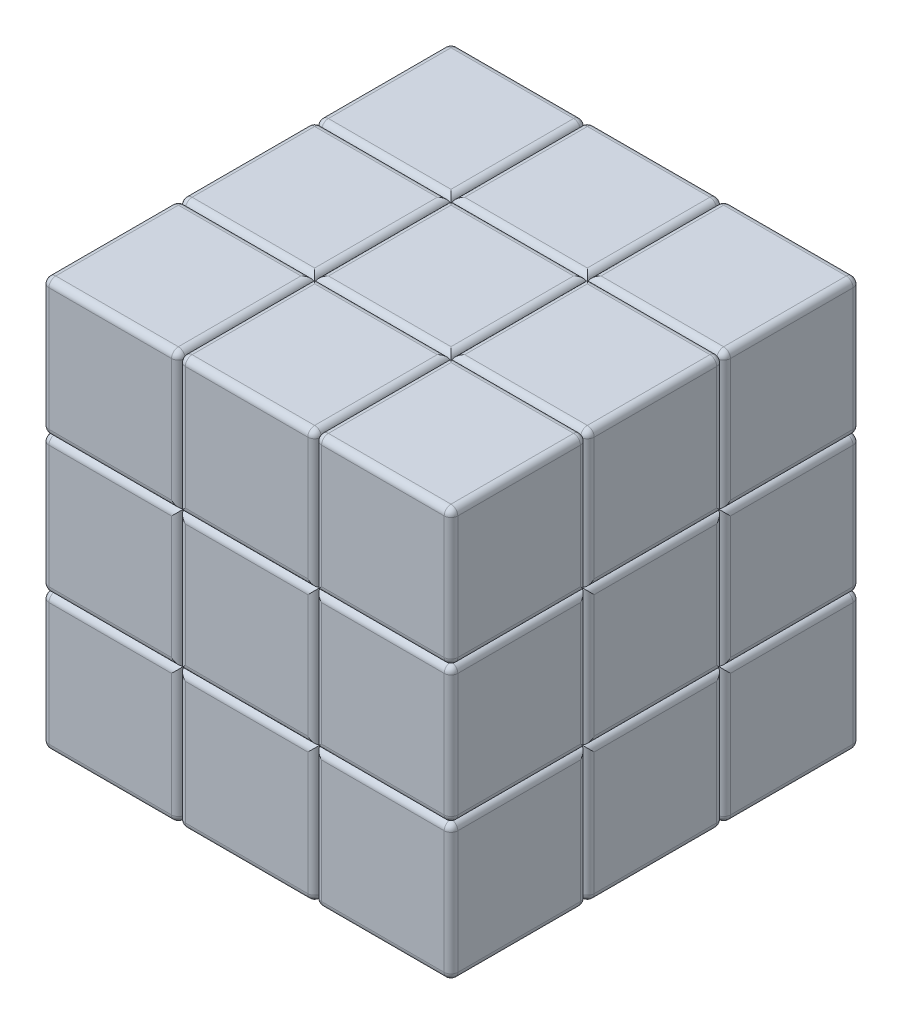
SolidWorks part; units mm, degrees
material "PA Type 6"
ref_plane "Front Plane" through (0, 0, 0) normal (0, 0, 1) x (1, 0, 0)
ref_plane "Top Plane" through (0, 0, 0) normal (0, 1, 0) x (1, 0, 0)
ref_plane "Right Plane" through (0, 0, 0) normal (1, 0, 0) x (0, 0, -1)
sketch "Sketch1" plane through (0, 0, 0) normal (0, 0, 1) x (1, 0, 0)
  line L1 (-41.2998, 31.3933) -> (18.7002, 31.3933)
  line L2 (-41.2998, 31.3933) -> (-41.2998, -28.6067)
  line L3 (-41.2998, -28.6067) -> (18.7002, -28.6067)
  line L4 (18.7002, 31.3933) -> (18.7002, -28.6067)
  dimension "D1" = 60
  dimension "D2" = 60
extrude "Boss-Extrude1" add sketch "Sketch1" along normal blind 60
sketch "Sketch2" plane through (0, 0, 60) normal (0, 0, 1) x (1, 0, 0)
  line L0 (-1.2898, -8.5967) -> (18.7002, -8.5967)
  line L3 (-21.2898, 11.3833) -> (-1.3098, 11.3833)
  line L4 (-21.2898, 11.3833) -> (-21.2898, -8.5967)
  line L7 (-1.2898, -8.6167) -> (18.7002, -8.6167)
  line L8 (-21.3098, 31.3933) -> (-21.3098, 11.4033)
  line L9 (-21.2898, 31.3933) -> (-21.2898, 11.4033)
  line L10 (-21.3098, 31.3933) -> (-21.2898, 31.3933)
  line L11 (-21.3098, -28.6067) -> (-21.2898, -28.6067)
  line L12 (-1.2898, -8.6167) -> (-1.2898, -28.6067)
  line L13 (-41.2998, 11.3833) -> (-21.3098, 11.3833)
  line L14 (-41.2998, -8.6167) -> (-21.3098, -8.6167)
  line L15 (-1.3098, 31.3933) -> (-1.3098, 11.4033)
  line L16 (-41.2998, 11.4033) -> (-21.3098, 11.4033)
  line L17 (-41.2998, -8.5967) -> (-21.3098, -8.5967)
  line L18 (-1.2898, 31.3933) -> (-1.2898, 11.4033)
  line L19 (-41.2998, 11.3833) -> (-41.2998, 11.4033)
  line L20 (18.7002, 11.3833) -> (18.7002, 11.4033)
  line L21 (-41.2998, -8.6167) -> (-41.2998, -8.5967)
  line L22 (18.7002, -8.6167) -> (18.7002, -8.5967)
  line L23 (-1.3098, 31.3933) -> (-1.2898, 31.3933)
  line L24 (-1.3098, -28.6067) -> (-1.2898, -28.6067)
  line L25 (-21.2898, -8.5967) -> (-1.3098, -8.5967)
  line L26 (-21.2898, 11.4033) -> (-1.3098, 11.4033)
  line L27 (-1.2898, 11.3833) -> (-1.2898, -8.5967)
  line L28 (-21.3098, 11.3833) -> (-21.3098, -8.5967)
  line L29 (-21.2898, -8.6167) -> (-1.3098, -8.6167)
  line L30 (-1.3098, -8.6167) -> (-1.3098, -28.6067)
  line L31 (-21.2898, -8.6167) -> (-21.2898, -28.6067)
  line L33 (-21.3098, -8.6167) -> (-21.3098, -28.6067)
  line L34 (-1.2898, 11.3833) -> (18.7002, 11.3833)
  line L35 (-1.3098, 11.3833) -> (-1.3098, -8.5967)
  line L38 (-1.2898, 11.4033) -> (18.7002, 11.4033)
extrude "Cut-Extrude1" cut sketch "Sketch2" against normal through all
sketch "Sketch4" plane through (18.7002, 0, 0) normal (1, 0, 0) x (0, 0, -1)
  line L4 (-40.01, 31.3933) -> (-40.01, -28.6067)
  line L5 (-20.01, 31.3933) -> (-20.01, -28.6067)
  line L6 (-39.99, 31.3933) -> (-39.99, -28.6067)
  line L7 (-19.99, 31.3933) -> (-19.99, -28.6067)
  line L8 (-40.01, 31.3933) -> (-39.99, 31.3933)
  line L9 (-40.01, -28.6067) -> (-39.99, -28.6067)
  line L10 (-20.01, 31.3933) -> (-19.99, 31.3933)
  line L11 (-20.01, -28.6067) -> (-19.99, -28.6067)
extrude "Cut-Extrude2" cut sketch "Sketch4" against normal through all
fillet "Fillet1" radius 1 9 edges at (-31.3048, 31.3933, 40.01) (-21.3098, 31.3933, 50.005) (-31.3048, 11.4033, 60) (-21.3098, 21.3983, 60) (-41.2998, 21.3983, 40.01) (-41.2998, 11.4033, 50.005) (-41.2998, 21.3983, 60) (-41.2998, 31.3933, 50.005) (-31.3048, 31.3933, 60)
fillet "Fillet2" radius 1 9 edges at (-1.2898, 31.3933, 50.005) (8.7052, 31.3933, 40.01) (18.7002, 31.3933, 50.005) (18.7002, 21.3983, 40.01) (18.7002, 11.4033, 50.005) (8.7052, 11.4033, 60) (-1.2898, 21.3983, 60) (18.7002, 21.3983, 60) (8.7052, 31.3933, 60)
fillet "Fillet3" radius 1 9 edges at (-1.2898, 21.3983, 0) (8.7052, 11.4033, 0) (18.7002, 21.3983, 0) (18.7002, 11.4033, 9.995) (18.7002, 21.3983, 19.99) (8.7052, 31.3933, 0) (18.7002, 31.3933, 9.995) (8.7052, 31.3933, 19.99) (-1.2898, 31.3933, 9.995)
fillet "Fillet4" radius 1 9 edges at (-41.2998, 21.3983, 19.99) (-41.2998, 11.4033, 9.995) (-21.3098, 31.3933, 9.995) (-31.3048, 31.3933, 19.99) (-41.2998, 31.3933, 9.995) (-31.3048, 31.3933, 0) (-41.2998, 21.3983, 0) (-31.3048, 11.4033, 0) (-21.3098, 21.3983, 0)
fillet "Fillet5" radius 1 9 edges at (18.7002, -18.6117, 19.99) (18.7002, -8.6167, 9.995) (18.7002, -18.6117, 0) (8.7052, -8.6167, 0) (-1.2898, -18.6117, 0) (8.7052, -28.6067, 0) (-1.2898, -28.6067, 9.995) (8.7052, -28.6067, 19.99) (18.7002, -28.6067, 9.995)
fillet "Fillet6" radius 1 9 edges at (-21.3098, -18.6117, 0) (-31.3048, -8.6167, 0) (-31.3048, -28.6067, 0) (-31.3048, -28.6067, 19.99) (-21.3098, -28.6067, 9.995) (-41.2998, -18.6117, 0) (-41.2998, -8.6167, 9.995) (-41.2998, -18.6117, 19.99) (-41.2998, -28.6067, 9.995)
fillet "Fillet7" radius 1 9 edges at (-41.2998, -18.6117, 40.01) (-41.2998, -8.6167, 50.005) (-41.2998, -18.6117, 60) (-31.3048, -8.6167, 60) (-21.3098, -18.6117, 60) (-31.3048, -28.6067, 60) (-21.3098, -28.6067, 50.005) (-31.3048, -28.6067, 40.01) (-41.2998, -28.6067, 50.005)
fillet "Fillet8" radius 1 9 edges at (18.7002, -8.6167, 50.005) (18.7002, -18.6117, 40.01) (18.7002, -18.6117, 60) (-1.2898, -18.6117, 60) (8.7052, -8.6167, 60) (8.7052, -28.6067, 60) (18.7002, -28.6067, 50.005) (8.7052, -28.6067, 40.01) (-1.2898, -28.6067, 50.005)
fillet "Fillet9" radius 1 7 edges at (18.7002, -18.6117, 20.01) (18.7002, -18.6117, 39.99) (18.7002, -8.6167, 30) (8.7052, -28.6067, 20.01) (-1.2898, -28.6067, 30) (8.7052, -28.6067, 39.99) (18.7002, -28.6067, 30)
fillet "Fillet10" radius 1 7 edges at (-21.2898, -18.6117, 0) (-1.3098, -18.6117, 0) (-11.2998, -8.6167, 0) (-11.2998, -28.6067, 0) (-21.2898, -28.6067, 9.995) (-11.2998, -28.6067, 19.99) (-1.3098, -28.6067, 9.995)
fillet "Fillet11" radius 1 7 edges at (-21.2898, -18.6117, 60) (-11.2998, -8.6167, 60) (-1.3098, -18.6117, 60) (-11.2998, -28.6067, 60) (-1.3098, -28.6067, 50.005) (-11.2998, -28.6067, 40.01) (-21.2898, -28.6067, 50.005)
fillet "Fillet12" radius 1 7 edges at (-31.3048, -28.6067, 20.01) (-31.3048, -28.6067, 39.99) (-21.3098, -28.6067, 30) (-41.2998, -18.6117, 20.01) (-41.2998, -8.6167, 30) (-41.2998, -18.6117, 39.99) (-41.2998, -28.6067, 30)
fillet "Fillet13" radius 1 4 edges at (-11.2998, -28.6067, 20.01) (-21.2898, -28.6067, 30) (-11.2998, -28.6067, 39.99) (-1.3098, -28.6067, 30)
fillet "Fillet14" radius 1 7 edges at (-31.3048, 31.3933, 20.01) (-21.3098, 31.3933, 30) (-31.3048, 31.3933, 39.99) (-41.2998, 21.3983, 20.01) (-41.2998, 31.3933, 30) (-41.2998, 21.3983, 39.99) (-41.2998, 11.4033, 30)
fillet "Fillet15" radius 1 7 edges at (-1.3098, 21.3983, 0) (-21.2898, 21.3983, 0) (-11.2998, 11.4033, 0) (-11.2998, 31.3933, 0) (-1.3098, 31.3933, 9.995) (-11.2998, 31.3933, 19.99) (-21.2898, 31.3933, 9.995)
fillet "Fillet16" radius 1 4 edges at (-11.2998, 31.3933, 20.01) (-1.3098, 31.3933, 30) (-11.2998, 31.3933, 39.99) (-21.2898, 31.3933, 30)
fillet "Fillet17" radius 1 7 edges at (18.7002, 21.3983, 20.01) (18.7002, 11.4033, 30) (18.7002, 21.3983, 39.99) (8.7052, 31.3933, 20.01) (18.7002, 31.3933, 30) (8.7052, 31.3933, 39.99) (-1.2898, 31.3933, 30)
fillet "Fillet18" radius 1 7 edges at (-21.2898, 31.3933, 50.005) (-11.2998, 31.3933, 40.01) (-1.3098, 31.3933, 50.005) (-11.2998, 31.3933, 60) (-1.3098, 21.3983, 60) (-11.2998, 11.4033, 60) (-21.2898, 21.3983, 60)
fillet "Fillet19" radius 1 7 edges at (18.7002, 11.3833, 50.005) (18.7002, 1.3933, 40.01) (18.7002, -8.5967, 50.005) (18.7002, 1.3933, 60) (8.7052, -8.5967, 60) (-1.2898, 1.3933, 60) (8.7052, 11.3833, 60)
fillet "Fillet20" radius 1 4 edges at (18.7002, 1.3933, 20.01) (18.7002, -8.5967, 30) (18.7002, 1.3933, 39.99) (18.7002, 11.3833, 30)
fillet "Fillet21" radius 1 7 edges at (8.7052, -8.5967, 0) (8.7052, 11.3833, 0) (-1.2898, 1.3933, 0) (18.7002, 1.3933, 0) (18.7002, -8.5967, 9.995) (18.7002, 1.3933, 19.99) (18.7002, 11.3833, 9.995)
fillet "Fillet22" radius 1 4 edges at (-11.2998, 11.3833, 0) (-21.2898, 1.3933, 0) (-11.2998, -8.5967, 0) (-1.3098, 1.3933, 0)
fillet "Fillet23" radius 1 7 edges at (-41.2998, 11.3833, 9.995) (-41.2998, 1.3933, 19.99) (-41.2998, -8.5967, 9.995) (-31.3048, 11.3833, 0) (-41.2998, 1.3933, 0) (-31.3048, -8.5967, 0) (-21.3098, 1.3933, 0)
fillet "Fillet24" radius 1 4 edges at (-41.2998, 1.3933, 20.01) (-41.2998, 11.3833, 30) (-41.2998, 1.3933, 39.99) (-41.2998, -8.5967, 30)
fillet "Fillet25" radius 1 7 edges at (-31.3048, 11.3833, 60) (-21.3098, 1.3933, 60) (-31.3048, -8.5967, 60) (-41.2998, 1.3933, 60) (-41.2998, -8.5967, 50.005) (-41.2998, 1.3933, 40.01) (-41.2998, 11.3833, 50.005)
fillet "Fillet26" radius 1 4 edges at (-21.2898, 1.3933, 60) (-11.2998, 11.3833, 60) (-1.3098, 1.3933, 60) (-11.2998, -8.5967, 60)
